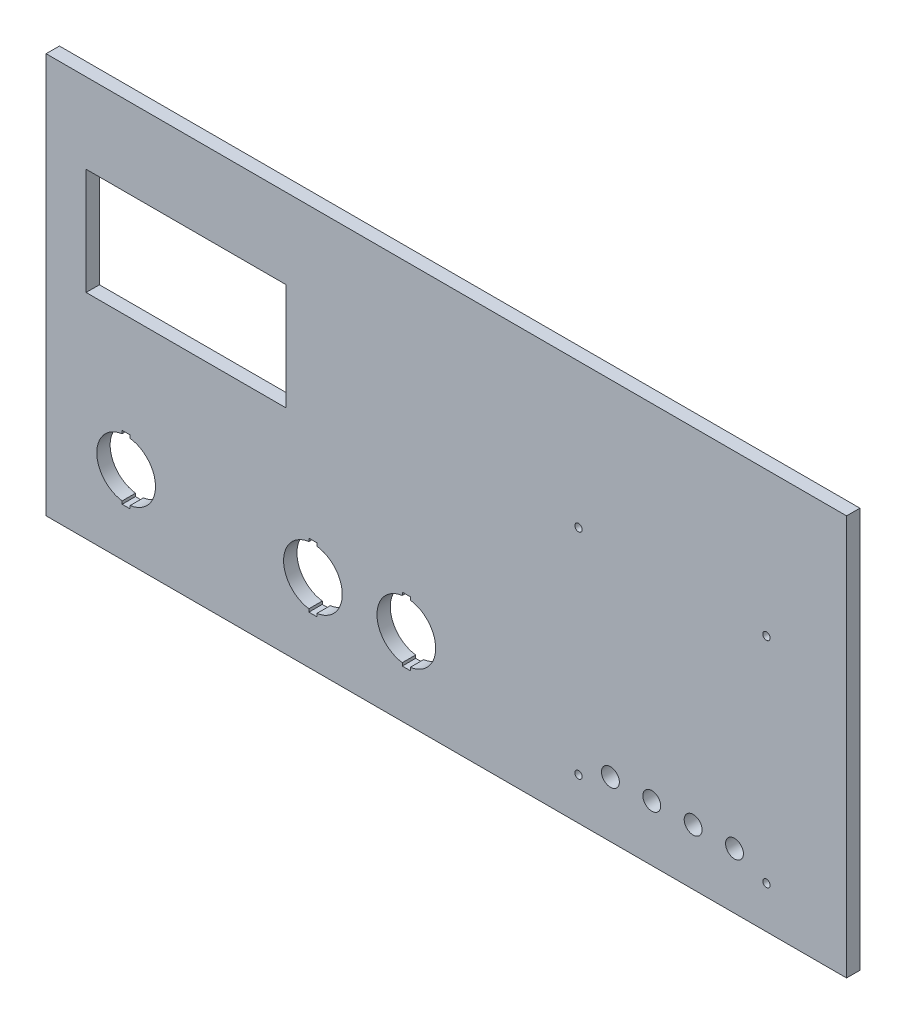
SolidWorks part; units mm, degrees
material "Glas"
ref_plane "Ebene vorne" through (0, 0, 0) normal (0, 0, 1) x (1, 0, 0)
ref_plane "Ebene oben" through (0, 0, 0) normal (0, 1, 0) x (1, 0, 0)
ref_plane "Ebene rechts" through (0, 0, 0) normal (1, 0, 0) x (0, 0, -1)
sketch "Skizze1" plane through (0, 0, 0) normal (0, 0, 1) x (1, 0, 0)
  line L1 (-150, 75) -> (150, 75)
  line L2 (-150, 75) -> (-150, -75)
  line L3 (-150, -75) -> (150, -75)
  line L4 (150, 75) -> (150, -75)
  line L5 (-150, 75) -> (150, -75) construction
  line L6 (-150, -75) -> (150, 75) construction
  point P0 (0, 0)
  dimension "D1" = 300
  dimension "D2" = 150
extrude "Aufsatz-Linear austragen1" add sketch "Skizze1" along normal blind 5
sketch "Skizze2" plane through (0, 0, 5) normal (0, 0, 1) x (1, 0, 0)
  line L1 (49.5373, -59.2618) -> (119.9627, 20.9618) construction
  line L2 (119.9627, -59.2618) -> (49.5373, 20.9618) construction
  line L3 (49.5373, 20.9618) -> (44.5, 26.7) construction
  line L4 (119.9627, 20.9618) -> (125, 26.7) construction
  line L5 (108, -54) -> (92.5, -54) construction
  line L6 (92.5, -54) -> (77, -54) construction
  line L7 (-150, -75) -> (150, -75) construction
  line L8 (150, -75) -> (150, 75) construction
  line L9 (44.5, 26.7) -> (125, 26.7) construction
  line L10 (44.5, 26.7) -> (44.5, -65) construction
  line L11 (44.5, -65) -> (125, -65) construction
  line L12 (125, 26.7) -> (125, -65) construction
  line L13 (84.75, -65) -> (84.75, 26.7) construction
  line L14 (44.5, -19.15) -> (125, -19.15) construction
  line L15 (77, -54) -> (61.5, -54) construction
  circle A0 centre (49.5373, 20.9618) radius 1.375
  circle A1 centre (119.9627, 20.9618) radius 1.375
  circle A2 centre (119.9627, -59.2618) radius 1.375
  circle A3 centre (49.5373, -59.2618) radius 1.375
  circle A4 centre (61.5, -54) radius 3.35
  circle A5 centre (77, -54) radius 3.35
  circle A6 centre (92.5, -54) radius 3.35
  circle A7 centre (108, -54) radius 3.35
  point P3 (84.75, -19.15)
  point P6 (84.75, -19.15)
  point P9 (84.75, -19.15)
  point P27 (84.75, -54)
  dimension "D1" = 2.75
  dimension "D3" = 6.7
  dimension "D2" = 106.75
  dimension "D4" = 15.5
  dimension "D5" = 80.5
  dimension "D6" = 91.7
  dimension "D7" = 10
  dimension "D8" = 25
  dimension "D9" = 11
sketch "Skizze3" plane through (0, 0, 5) normal (0, 0, 1) x (1, 0, 0)
  line L0 (150, 75) -> (-150, 75) construction
  line L1 (-135, 45) -> (-60, 45)
  line L2 (-135, 45) -> (-135, 5)
  line L3 (-135, 5) -> (-60, 5)
  line L4 (-60, 45) -> (-60, 5)
  line L5 (-135, 45) -> (-60, 5) construction
  line L6 (-135, 5) -> (-60, 45) construction
  line L7 (-150, 75) -> (-150, -75) construction
  point P0 (-97.5, 25)
  dimension "D1" = 75
  dimension "D2" = 40
  dimension "D3" = 30
  dimension "D4" = 15
extrude "Schnitt-Linear austragen2" cut sketch "Skizze3" against normal through all
sketch "Skizze5" plane through (0, 0, 5) normal (0, 0, 1) x (1, 0, 0)
  line L0 (-150, -45) -> (0, -45) construction
  line L3 (-150, -75) -> (150, -75) construction
  line L4 (-150, 75) -> (-150, -75) construction
  line L5 (-13.5, -57) -> (-16.5, -57)
  line L6 (-13.5, -57) -> (-13.5, -33)
  line L8 (-13.5, -33) -> (-16.5, -33)
  line L9 (-16.5, -57) -> (-16.5, -33)
  line L10 (-13.5, -57) -> (-16.5, -33) construction
  line L11 (-13.5, -33) -> (-16.5, -57) construction
  line L12 (-48.5, -57) -> (-51.5, -57)
  line L13 (-48.5, -57) -> (-48.5, -33)
  line L14 (-48.5, -33) -> (-51.5, -33)
  line L15 (-51.5, -57) -> (-51.5, -33)
  line L16 (-48.5, -57) -> (-51.5, -33) construction
  line L17 (-48.5, -33) -> (-51.5, -57) construction
  line L18 (-118.5, -57) -> (-121.5, -57)
  line L19 (-118.5, -57) -> (-118.5, -33)
  line L20 (-118.5, -33) -> (-121.5, -33)
  line L21 (-121.5, -57) -> (-121.5, -33)
  line L22 (-118.5, -57) -> (-121.5, -33) construction
  line L23 (-118.5, -33) -> (-121.5, -57) construction
  circle A0 centre (-15, -45) radius 11
  circle A1 centre (-50, -45) radius 11
  circle A2 centre (-120, -45) radius 11
  point P2 (0, 0)
  point P5 (0, 0)
  dimension "D1" = 22
  dimension "D4" = 30
  dimension "D3" = 70
  dimension "D2" = 35
  dimension "D5" = 3
  dimension "D6" = 24
  dimension "D8" = 30
extrude "Schnitt-Linear austragen4" cut sketch "Skizze5" against normal through all contours L21 A2 | L19 A2 | L6 A0 | L9 A0 | L6 A0 L9 | A1 | L14 L15 L12 L13
extrude "Schnitt-Linear austragen5" cut sketch "Skizze2" against normal through all
